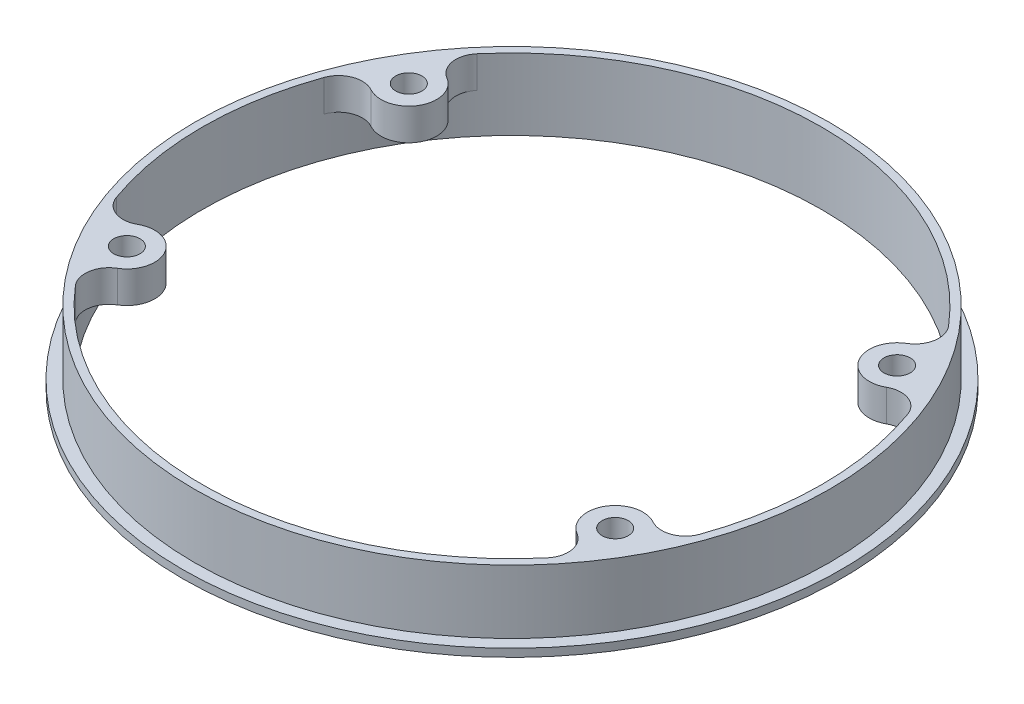
SolidWorks part; units mm, degrees
material "6061 合金"
ref_plane "前视基准面" through (0, 0, 0) normal (0, 0, 1) x (1, 0, 0)
ref_plane "上视基准面" through (0, 0, 0) normal (0, 1, 0) x (1, 0, 0)
ref_plane "右视基准面" through (0, 0, 0) normal (1, 0, 0) x (0, 0, -1)
sketch "草图1" plane through (0, 0, 0) normal (0, 0, 1) x (1, 0, 0)
  line L0 (-41.5, 0) -> (-39, 0)
  line L2 (-40, 9) -> (-32, 9)
  line L4 (-32, 5) -> (-39, 5)
  line L5 (-39, 5) -> (-39, 0)
  line L6 (0, 0) -> (0, 11.4496) construction
  line L11 (-40, 1) -> (-41.5, 1)
  line L12 (-41.5, 1) -> (-41.5, 0)
  line L14 (-40, 9) -> (-40, 1)
  line L17 (-32, 5) -> (-32, 9)
  dimension "D1" = 8
  dimension "D2" = 7
  dimension "D3" = 80
  dimension "D4" = 4
  dimension "D5" = 1.5
  dimension "D6" = 1
  dimension "D8" = 1
revolve "旋转1" add sketch "草图1" angle 360 about L6
hole_wizard "M4 螺纹孔1" positions "草图2" profile "草图3" tap size "M4" standard "GB" end condition through all
sketch "草图2" plane through (0, 9, 0) normal (0, -1, 0) x (-1, 0, 0)
  circle A0 centre (0, 0) radius 35.5 construction
  circle A3 centre (0, 0) radius 32 construction
  point P0 (0, 35.5)
  point P12 (30.7439, 17.75)
  point P13 (30.7439, -17.75)
  point P14 (0, -35.5)
  point P24 (-30.7439, -17.75)
  point P25 (-30.7439, 17.75)
  dimension "D1" = 3.5
  dimension "D2" = 6
cosmetic thread "孔螺蚊线5" parameters "D2"=4
cosmetic thread "孔螺蚊线6" parameters "D2"=4
cosmetic thread "孔螺蚊线7" parameters "D2"=4
cosmetic thread "孔螺蚊线8" parameters "D2"=4
sketch "草图3" plane through (0, 9, -35.5) normal (1, 0, 0) x (0, 0, 1)
  line L0 (0, 0) -> (0, 9)
  line L1 (0, 9) -> (1.65, 9)
  line L2 (1.65, 9) -> (1.65, 0)
  line L5 (1.65, 0) -> (0, 0)
  line L11 (0, -6.35) -> (0, 107.95) construction
  dimension "通孔螺纹孔钻头直径" = 3.3
  dimension "通孔螺纹孔钻头深度" = 9
cosmetic thread "孔螺蚊线9" parameters "D2"=4
cosmetic thread "孔螺蚊线10" parameters "D2"=4
sketch "草图4" plane through (0, 9, 0) normal (0, 1, 0) x (1, 0, 0)
  line L0 (-4.95, 0) -> (4.95, 0) construction
  arc A0 (-32.451, 14.6946) -> (-28.9514, 20.7561) centre (-30.7439, 17.75) ccw
  circle A1 centre (0, 0) radius 32 construction
  arc A2 (-36.7405, 13.0819) -> (-36.7405, -13.0819) centre (0, 0) ccw
  arc A3 (3.4997, -35.4507) -> (-3.4997, -35.4507) centre (0, -35.5) ccw construction
  arc A6 (-3.4997, 35.4507) -> (3.4997, 35.4507) centre (0, 35.5) ccw construction
  arc A7 (-32.451, 14.6946) -> (-36.7405, 13.0819) centre (-33.9143, 12.0756) ccw
  arc A8 (-28.9514, 20.7561) -> (-29.6995, 25.2772) centre (-27.4149, 23.3328) cw
  arc A9 (-7.041, 38.3592) -> (-29.6995, 25.2772) centre (0, 0) ccw
  arc A10 (28.9514, 20.7561) -> (32.451, 14.6946) centre (30.7439, 17.75) ccw
  arc A11 (-3.4997, 35.4507) -> (-7.041, 38.3592) centre (-6.4994, 35.4085) ccw construction
  arc A12 (3.4997, 35.4507) -> (7.041, 38.3592) centre (6.4994, 35.4085) cw construction
  arc A13 (29.6995, 25.2772) -> (7.041, 38.3592) centre (0, 0) ccw
  arc A14 (32.451, -14.6946) -> (28.9514, -20.7561) centre (30.7439, -17.75) ccw
  arc A15 (28.9514, 20.7561) -> (29.6995, 25.2772) centre (27.4149, 23.3328) ccw
  arc A16 (32.451, 14.6946) -> (36.7405, 13.0819) centre (33.9143, 12.0756) cw
  arc A17 (36.7405, -13.0819) -> (36.7405, 13.0819) centre (0, 0) ccw
  arc A18 (7.041, -38.3592) -> (29.6995, -25.2772) centre (0, 0) ccw
  arc A19 (32.451, -14.6946) -> (36.7405, -13.0819) centre (33.9143, -12.0756) ccw
  arc A20 (28.9514, -20.7561) -> (29.6995, -25.2772) centre (27.4149, -23.3328) cw
  circle A21 centre (0, 0) radius 39 construction
  arc A22 (3.4997, -35.4507) -> (7.041, -38.3592) centre (6.4994, -35.4085) ccw construction
  arc A23 (-3.4997, -35.4507) -> (-7.041, -38.3592) centre (-6.4994, -35.4085) cw construction
  arc A24 (-28.9514, -20.7561) -> (-32.451, -14.6946) centre (-30.7439, -17.75) ccw
  arc A25 (-29.6995, -25.2772) -> (-7.041, -38.3592) centre (0, 0) ccw
  arc A26 (-28.9514, -20.7561) -> (-29.6995, -25.2772) centre (-27.4149, -23.3328) ccw
  arc A27 (-32.451, -14.6946) -> (-36.7405, -13.0819) centre (-33.9143, -12.0756) cw
  arc A28 (-7.041, 38.3592) -> (7.041, 38.3592) centre (0, 0) cw
  arc A29 (-7.041, -38.3592) -> (7.041, -38.3592) centre (0, 0) ccw
  dimension "D2" = 6
  dimension "D3" = 3
extrude "切除-拉伸1" cut sketch "草图4" against normal through all
